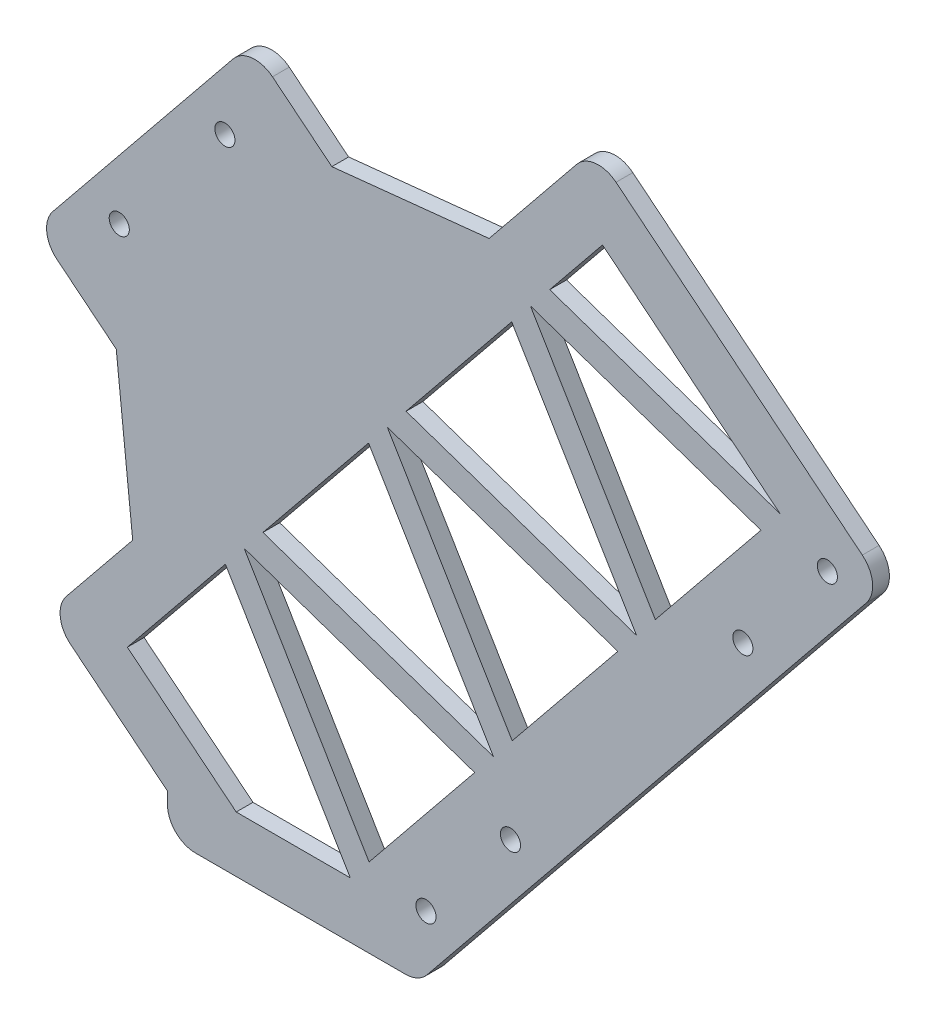
SolidWorks part; units mm, degrees
ref_plane "Front Plane" through (0, 0, 0) normal (0, 0, 1) x (1, 0, 0)
ref_plane "Top Plane" through (0, 0, 0) normal (0, 1, 0) x (1, 0, 0)
ref_plane "Right Plane" through (0, 0, 0) normal (1, 0, 0) x (0, 0, -1)
sketch "Sketch3" plane through (0, 0, -35.5044) normal (0, 0, -1) x (-1, 0, 0)
  line L0 (-347.2055, 177.752) -> (-353.0755, 184.9904) construction
  line L1 (-347.2055, 177.752) -> (-315.7124, 138.9166) construction
  line L2 (-290.2529, 107.5217) -> (-315.7124, 138.9166) construction
  line L3 (-227.2667, 29.851) -> (-290.2529, 107.5217) construction
  line L4 (-347.2055, 177.752) -> (-353.0755, 184.9904) construction
  line L5 (-347.2055, 177.752) -> (-315.7124, 138.9166) construction
  line L6 (-290.2529, 107.5217) -> (-315.7124, 138.9166) construction
  line L7 (-227.2667, 29.851) -> (-290.2529, 107.5217) construction
  line L8 (-263.2453, 74.5) -> (20.7547, 74.5) construction
  line L9 (-263.2453, 74.5) -> (20.7547, 74.5) construction
  line L10 (-218.45, 74.7) -> (-263.379, 74.7)
  line L11 (-263.379, 74.7) -> (-346.6215, 177.3493)
  line L12 (-346.6215, 177.3493) -> (-294.7977, 219.3753)
  line L14 (-218.45, 81.7917) -> (-218.45, 74.7)
  line L15 (-218.25, 74.5) -> (-218.25, 79.5) construction
  line L16 (-218.25, 74.5) -> (-218.25, 79.5) construction
  line L17 (-197.2001, 99.0241) -> (-224.8166, 133.0791)
  line L18 (-218.45, 81.7917) -> (-197.2001, 99.0241)
  line L19 (-263.379, 180.6318) -> (-233.3456, 204.9871)
  line L20 (-233.3456, 204.9871) -> (-194.7832, 157.4344)
  line L21 (-194.7832, 157.4344) -> (-224.8166, 133.0791)
  line L22 (-263.379, 180.6318) -> (-294.7977, 219.3753)
  line L23 (-224.8166, 133.0791) -> (-263.379, 180.6318) construction
  point P22 (-279.2277, 245.0495)
  point P29 (-271.8277, 245.0495)
  dimension "D1" = 0.2
  dimension "D2" = 0.2
  dimension "D3" = 0.2
  dimension "D4" = 10
extrude "Boss-Extrude1" add sketch "Sketch3" along normal blind 3 from surface at -0.5044
sketch "Sketch4" plane through (0, 0, -38) normal (0, 0, -1) x (-1, 0, 0)
  point P0 (-264.6838, 86.3112)
  point P3 (-279.8005, 104.9521)
  point P6 (-321.3715, 156.2147)
  point P9 (-336.4882, 174.8557)
hole_wizard "M3 Clearance Hole1" positions "Sketch4" profile "Sketch5" hole size "M3" standard "ANSI Metric" end condition through all
sketch "Sketch5" plane through (264.6838, 86.3112, -38) normal (1, 0, 0) x (0, 1, 0)
  line L0 (0, 0) -> (0, 3)
  line L1 (0, 3) -> (1.8, 3)
  line L2 (1.8, 3) -> (1.8, 0)
  line L5 (1.8, 0) -> (0, 0)
  line L11 (0, -6.35) -> (0, 107.95) construction
  dimension "Thru Hole Dia." = 3.6
  dimension "Thru Hole Depth" = 3
sketch "Sketch8" plane through (0, 0, -38) normal (0, 0, -1) x (-1, 0, 0)
  line L0 (-233.3456, 204.9871) -> (-194.7832, 157.4344) construction
  line L1 (-282.3169, 238.5129) -> (-163.0892, 90.9635) construction
  line L2 (-233.3456, 204.9871) -> (-194.7832, 157.4344) construction
  line L3 (-282.3169, 238.5129) -> (-163.0892, 90.9635) construction
  line L4 (-266.1386, 251.5859) -> (-146.9108, 104.0365) construction
  line L5 (-266.1386, 251.5859) -> (-146.9108, 104.0365) construction
  line L6 (-227.336, 170.4717) -> (-211.1577, 183.5446) construction
  line L7 (-238.4865, 200.8181) -> (-200.0071, 153.1982) construction
  line L8 (-194.7832, 157.4344) -> (-224.8166, 133.0791) construction
  line L9 (-263.379, 180.6318) -> (-233.3456, 204.9871) construction
  point P13 (-219.2468, 177.0081)
chamfer "Chamfer1" distance 20 angle 45 2 edges at (224.8166, 133.0791, -36.5) (263.379, 180.6318, -36.5)
sketch "Sketch11" plane through (0, 0, -38) normal (0, 0, -1) x (-1, 0, 0)
  line L0 (-296.2661, 205.3096) -> (-211.2658, 100.4926)
  line L1 (-211.2658, 100.4926) -> (-230.7401, 84.7)
  line L2 (-230.7401, 84.7) -> (-251.1461, 84.7)
  line L3 (-251.1461, 84.7) -> (-328.0509, 179.534)
  line L4 (-328.0509, 179.534) -> (-296.2661, 205.3096)
  line L5 (-335.1975, 180.4086) -> (-330.7885, 174.9716) construction
  line L6 (-335.1975, 180.4086) -> (-330.7885, 174.9716) construction
  line L7 (-251.1461, 84.7) -> (-228.8093, 122.1262)
  line L8 (-254.5003, 88.8362) -> (-232.1635, 126.2624)
  line L9 (-232.1635, 126.2624) -> (-273.3962, 112.1374)
  line L10 (-235.5177, 130.3986) -> (-276.7504, 116.2736)
  line L11 (-276.7504, 116.2736) -> (-254.4136, 153.6997)
  line L12 (-280.1047, 120.4098) -> (-257.7678, 157.8359)
  line L13 (-268.9362, 139.1229) -> (-264.6428, 136.5604) construction
  line L14 (-256.1341, 123.3361) -> (-254.5137, 118.6059) construction
  line L15 (-243.3319, 107.5493) -> (-239.0385, 104.9868) construction
  line L16 (-257.7678, 157.8359) -> (-299.0005, 143.711)
  line L17 (-263.379, 74.7) -> (-218.45, 74.7)
  line L18 (-218.45, 74.7) -> (-218.45, 81.7917)
  line L19 (-218.45, 81.7917) -> (-197.2001, 99.0241)
  line L20 (-197.2001, 99.0241) -> (-212.2194, 117.545)
  line L22 (-209.2825, 145.6764) -> (-194.7832, 157.4344)
  line L23 (-194.7832, 157.4344) -> (-233.3456, 204.9871)
  line L24 (-233.3456, 204.9871) -> (-247.8449, 193.229)
  line L26 (-275.9763, 196.1659) -> (-294.7977, 219.3753)
  line L27 (-294.7977, 219.3753) -> (-346.6215, 177.3493)
  line L28 (-346.6215, 177.3493) -> (-263.379, 74.7)
  line L29 (-263.379, 74.7) -> (-218.45, 74.7) construction
  line L30 (-218.45, 74.7) -> (-218.45, 81.7917) construction
  line L31 (-218.45, 81.7917) -> (-197.2001, 99.0241) construction
  line L32 (-197.2001, 99.0241) -> (-212.2194, 117.545) construction
  line L34 (-209.2825, 145.6764) -> (-194.7832, 157.4344) construction
  line L35 (-194.7832, 157.4344) -> (-233.3456, 204.9871) construction
  line L36 (-233.3456, 204.9871) -> (-247.8449, 193.229) construction
  line L38 (-275.9763, 196.1659) -> (-294.7977, 219.3753) construction
  line L39 (-294.7977, 219.3753) -> (-346.6215, 177.3493) construction
  line L40 (-346.6215, 177.3493) -> (-263.379, 74.7) construction
  line L41 (-261.122, 161.9721) -> (-302.3548, 147.8472)
  line L42 (-278.3842, 150.7735) -> (-280.0046, 155.5036) construction
  line L43 (-302.3548, 147.8472) -> (-280.0179, 185.2733)
  line L44 (-305.709, 151.9834) -> (-283.3721, 189.4095)
  line L45 (-291.1863, 166.5603) -> (-295.4798, 169.1227) construction
  line L46 (-283.3721, 189.4095) -> (-324.6049, 175.2846)
  line L47 (-328.0509, 179.534) -> (-286.8182, 193.659)
  line L58 (-212.2194, 117.545) -> (-209.2825, 145.6764)
  line L59 (-212.2194, 117.545) -> (-209.2825, 145.6764)
  line L60 (-247.8449, 193.229) -> (-275.9763, 196.1659)
  line L61 (-247.8449, 193.229) -> (-275.9763, 196.1659)
  dimension "D2" = 10
  dimension "D3" = 10
  dimension "D4" = 5
  dimension "D5" = 10
  dimension "D6" = 10
  dimension "D7" = 30
  dimension "D8" = 30
  dimension "D9" = 5
  dimension "D10" = 30
  dimension "D1" = 0
extrude "Cut-Extrude1" cut sketch "Sketch11" against normal blind 9 contours L7 L2 L1 L0 | L8 L9 L3 | L11 L10 L0 | L12 L16 L3 | L43 L41 L0 | L44 L46 L3 | L4 L47 L0
fillet "Fillet1" radius 5 7 edges at (346.6215, 177.3493, -36.5) (218.45, 74.7, -36.5) (197.2001, 99.0241, -36.5) (194.7832, 157.4344, -36.5) (233.3456, 204.9871, -36.5) (294.7977, 219.3753, -36.5) (263.379, 74.7, -36.5)
sketch "Sketch9" plane through (0, 0, -38) normal (0, 0, -1) x (-1, 0, 0)
  line L0 (-238.4865, 200.8181) -> (-200.0071, 153.1982) construction
  line L1 (-214.0644, 181.2108) -> (-225.8286, 171.6707) construction
  line L2 (-230.1963, 201.1036) -> (-197.9325, 161.318) construction
  line L4 (-233.3456, 204.9871) -> (-194.7832, 157.4344) construction
  point P0 (-209.8192, 165.3411)
  point P14 (-228.7151, 188.6422)
  dimension "D1" = 15
hole_wizard "M3 Clearance Hole2" positions "Sketch9" profile "Sketch10" hole size "M3" standard "ANSI Metric" end condition through all
sketch "Sketch10" plane through (209.8192, 165.3411, -38) normal (1, 0, 0) x (0, 1, 0)
  line L0 (0, 0) -> (0, 3)
  line L1 (0, 3) -> (1.8, 3)
  line L2 (1.8, 3) -> (1.8, 0)
  line L5 (1.8, 0) -> (0, 0)
  line L11 (0, -6.35) -> (0, 107.95) construction
  dimension "Thru Hole Dia." = 3.6
  dimension "Thru Hole Depth" = 3
